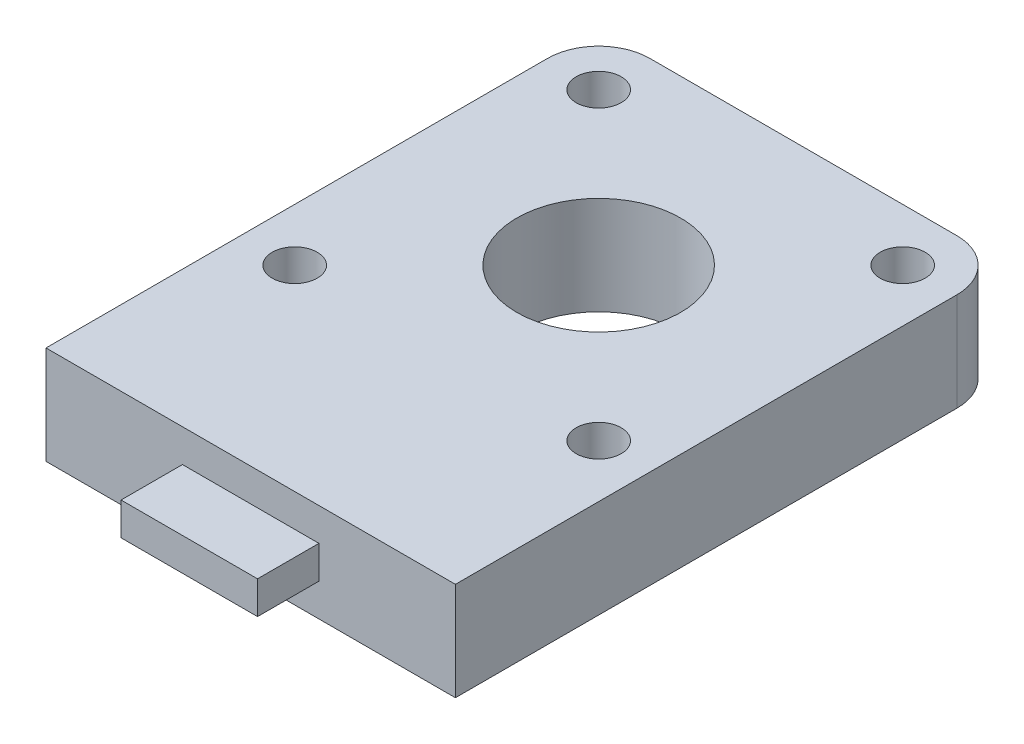
SolidWorks part; units mm, degrees
material "PF"
ref_plane "前视基准面" through (0, 0, 0) normal (0, 0, 1) x (1, 0, 0)
ref_plane "上视基准面" through (0, 0, 0) normal (0, 1, 0) x (1, 0, 0)
ref_plane "右视基准面" through (0, 0, 0) normal (1, 0, 0) x (0, 0, -1)
sketch "草图1" plane through (0, 0, 0) normal (0, 1, 0) x (1, 0, 0)
  line L0 (-10, -17) -> (10, -17)
  line L1 (-10, -17) -> (-10, 10)
  line L2 (10, -17) -> (10, 10)
  line L3 (-10, 10) -> (10, 10)
  line L4 (0, -17) -> (0, 0) construction
  line L5 (0, 0) -> (7.4246, 7.4246) construction
  circle A0 centre (7.4246, 7.4246) radius 1.1
  circle A1 centre (7.4246, -7.4246) radius 1.1
  circle A2 centre (-7.4246, -7.4246) radius 1.1
  circle A3 centre (-7.4246, 7.4246) radius 1.1
  circle A4 centre (0, 0) radius 4
  point P1 (0, 0)
  dimension "D4" = 4
  dimension "D1" = 20
  dimension "D2" = 27
  dimension "D3" = 10.5
extrude "凸台-拉伸1" add sketch "草图1" along normal blind 4.8
fillet "圆角3" radius 2.5 1 edges at (-10, 2.4, -10)
fillet "圆角4" radius 2.5 1 edges at (10, 2.4, -10)
sketch "草图2" plane through (0, 0, 17) normal (0, 0, 1) x (1, 0, 0)
  line L0 (-3.3333, 3.2) -> (3.3333, 3.2)
  line L1 (-3.3333, 3.2) -> (-3.3333, 1.6)
  line L2 (3.3333, 3.2) -> (3.3333, 1.6)
  line L3 (-3.3333, 1.6) -> (3.3333, 1.6)
  line L4 (-10, 2.4) -> (-3.3333, 2.4) construction
  line L5 (-10, 4.8) -> (-10, 0) construction
  line L6 (3.3333, 2.2042) -> (10, 2.2042) construction
  line L7 (10, 4.8) -> (10, 0) construction
  line L8 (-2.1275, 4.8) -> (-2.1275, 3.2) construction
  line L9 (-10, 4.8) -> (10, 4.8) construction
  line L10 (-2.7727, 1.6) -> (-2.7727, 0) construction
  line L11 (-10, 0) -> (10, 0) construction
extrude "凸台-拉伸2" add sketch "草图2" along normal blind 3
